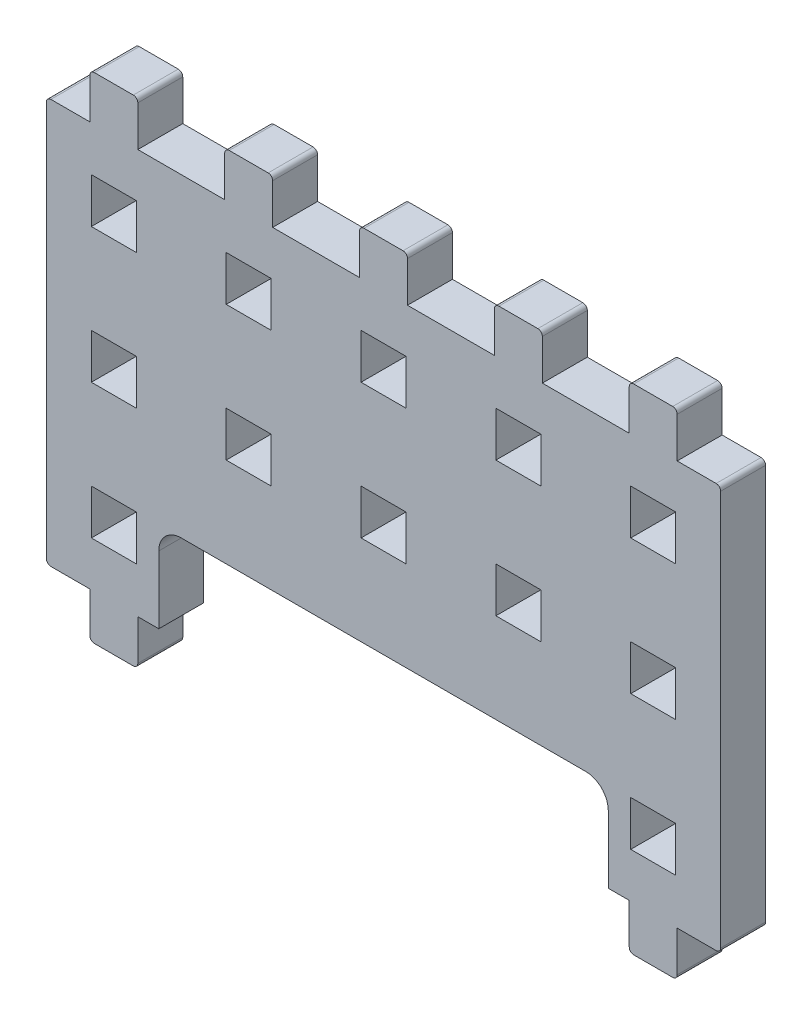
SolidWorks part; units mm, degrees
ref_plane "Alzado" through (0, 0, 0) normal (0, 0, 1) x (1, 0, 0)
ref_plane "Planta" through (0, 0, 0) normal (0, 1, 0) x (1, 0, 0)
ref_plane "Vista lateral" through (0, 0, 0) normal (1, 0, 0) x (0, 0, -1)
sketch "Model" plane through (0, 0, 0) normal (0, 0, 1) x (1, 0, 0)
  line L0 (12.4787, 293.1223) -> (12.4787, 290.1223)
  line L1 (15.4787, 293.1223) -> (12.4787, 293.1223)
  line L2 (15.4787, 290.1223) -> (15.4787, 293.1223)
  line L3 (12.4787, 290.1223) -> (15.4787, 290.1223)
  line L4 (21.4787, 293.1223) -> (21.4787, 290.1223)
  line L5 (24.4787, 293.1223) -> (21.4787, 293.1223)
  line L6 (24.4787, 290.1223) -> (24.4787, 293.1223)
  line L7 (21.4787, 290.1223) -> (24.4787, 290.1223)
  line L8 (30.4787, 293.1223) -> (30.4787, 290.1223)
  line L9 (33.4787, 293.1223) -> (30.4787, 293.1223)
  line L10 (33.4787, 290.1223) -> (33.4787, 293.1223)
  line L11 (30.4787, 290.1223) -> (33.4787, 290.1223)
  line L12 (12.4787, 275.1223) -> (12.4787, 272.1223)
  line L13 (15.4787, 275.1223) -> (12.4787, 275.1223)
  line L14 (15.4787, 272.1223) -> (15.4787, 275.1223)
  line L15 (12.4787, 272.1223) -> (15.4787, 272.1223)
  line L16 (12.4787, 284.1223) -> (12.4787, 281.1223)
  line L17 (15.4787, 284.1223) -> (12.4787, 284.1223)
  line L18 (15.4787, 281.1223) -> (15.4787, 284.1223)
  line L19 (12.4787, 281.1223) -> (15.4787, 281.1223)
  line L20 (21.4787, 284.1223) -> (21.4787, 281.1223)
  line L21 (24.4787, 284.1223) -> (21.4787, 284.1223)
  line L22 (24.4787, 281.1223) -> (24.4787, 284.1223)
  line L23 (21.4787, 281.1223) -> (24.4787, 281.1223)
  line L24 (30.4787, 284.1223) -> (30.4787, 281.1223)
  line L25 (33.4787, 284.1223) -> (30.4787, 284.1223)
  line L26 (33.4787, 281.1223) -> (33.4787, 284.1223)
  line L27 (30.4787, 281.1223) -> (33.4787, 281.1223)
  line L28 (48.4787, 293.1223) -> (48.4787, 290.1223)
  line L29 (51.4787, 293.1223) -> (48.4787, 293.1223)
  line L30 (51.4787, 290.1223) -> (51.4787, 293.1223)
  line L31 (48.4787, 290.1223) -> (51.4787, 290.1223)
  line L32 (48.4787, 275.1223) -> (48.4787, 272.1223)
  line L33 (51.4787, 275.1223) -> (48.4787, 275.1223)
  line L34 (51.4787, 272.1223) -> (51.4787, 275.1223)
  line L35 (48.4787, 272.1223) -> (51.4787, 272.1223)
  line L36 (48.4787, 284.1223) -> (48.4787, 281.1223)
  line L37 (51.4787, 284.1223) -> (48.4787, 284.1223)
  line L38 (51.4787, 281.1223) -> (51.4787, 284.1223)
  line L39 (48.4787, 281.1223) -> (51.4787, 281.1223)
  line L40 (39.4787, 293.1223) -> (39.4787, 290.1223)
  line L41 (42.4787, 293.1223) -> (39.4787, 293.1223)
  line L42 (42.4787, 290.1223) -> (42.4787, 293.1223)
  line L43 (39.4787, 290.1223) -> (42.4787, 290.1223)
  line L44 (39.4787, 284.1223) -> (39.4787, 281.1223)
  line L45 (42.4787, 284.1223) -> (39.4787, 284.1223)
  line L46 (42.4787, 281.1223) -> (42.4787, 284.1223)
  line L47 (39.4787, 281.1223) -> (42.4787, 281.1223)
  line L48 (9.4787, 295.8223) -> (9.4787, 269.4223)
  line L49 (12.3787, 298.8223) -> (12.3787, 296.1223)
  line L50 (15.5787, 296.1223) -> (15.5787, 298.8223)
  line L51 (12.6787, 299.1223) -> (15.2787, 299.1223)
  line L52 (9.7787, 296.1223) -> (12.3787, 296.1223)
  line L53 (24.5787, 296.1223) -> (30.3787, 296.1223)
  line L54 (21.3787, 298.8223) -> (21.3787, 296.1223)
  line L55 (24.5787, 296.1223) -> (24.5787, 298.8223)
  line L56 (21.6787, 299.1223) -> (24.2787, 299.1223)
  line L57 (15.5787, 296.1223) -> (21.3787, 296.1223)
  line L58 (30.3787, 298.8223) -> (30.3787, 296.1223)
  line L59 (33.5787, 296.1223) -> (33.5787, 298.8223)
  line L60 (30.6787, 299.1223) -> (33.2787, 299.1223)
  line L61 (12.3787, 266.4223) -> (12.3787, 269.1223)
  line L62 (15.5787, 269.1223) -> (15.5787, 266.4223)
  line L63 (12.6787, 266.1223) -> (15.2787, 266.1223)
  line L64 (9.7787, 269.1223) -> (12.3787, 269.1223)
  line L65 (46.9787, 269.1223) -> (48.3787, 269.1223)
  line L66 (54.4787, 295.8223) -> (54.4787, 269.4223)
  line L67 (33.5787, 296.1223) -> (39.3787, 296.1223)
  line L68 (48.3787, 298.8223) -> (48.3787, 296.1223)
  line L69 (51.5787, 296.1223) -> (51.5787, 298.8223)
  line L70 (48.6787, 299.1223) -> (51.2787, 299.1223)
  line L71 (51.5787, 296.1223) -> (54.1787, 296.1223)
  line L72 (48.3787, 266.4223) -> (48.3787, 269.1223)
  line L73 (51.5787, 269.1223) -> (51.5787, 266.4223)
  line L74 (48.6787, 266.1223) -> (51.2787, 266.1223)
  line L75 (51.5787, 269.1223) -> (54.1787, 269.1223)
  line L76 (18.4787, 275.1223) -> (45.4787, 275.1223)
  line L77 (16.9787, 273.6223) -> (16.9787, 269.1223)
  line L78 (46.9787, 273.6223) -> (46.9787, 269.1223)
  line L79 (15.5787, 269.1223) -> (16.9787, 269.1223)
  line L80 (39.3787, 298.8223) -> (39.3787, 296.1223)
  line L81 (42.5787, 296.1223) -> (42.5787, 298.8223)
  line L82 (39.6787, 299.1223) -> (42.2787, 299.1223)
  line L83 (42.5787, 296.1223) -> (48.3787, 296.1223)
  arc A0 (12.6787, 299.1223) -> (12.3787, 298.8223) centre (12.6787, 298.8223) ccw
  arc A1 (15.5787, 298.8223) -> (15.2787, 299.1223) centre (15.2787, 298.8223) ccw
  arc A2 (9.7787, 296.1223) -> (9.4787, 295.8223) centre (9.7787, 295.8223) ccw
  arc A3 (21.6787, 299.1223) -> (21.3787, 298.8223) centre (21.6787, 298.8223) ccw
  arc A4 (24.5787, 298.8223) -> (24.2787, 299.1223) centre (24.2787, 298.8223) ccw
  arc A5 (30.6787, 299.1223) -> (30.3787, 298.8223) centre (30.6787, 298.8223) ccw
  arc A6 (33.5787, 298.8223) -> (33.2787, 299.1223) centre (33.2787, 298.8223) ccw
  arc A7 (12.3787, 266.4223) -> (12.6787, 266.1223) centre (12.6787, 266.4223) ccw
  arc A8 (15.2787, 266.1223) -> (15.5787, 266.4223) centre (15.2787, 266.4223) ccw
  arc A9 (9.4787, 269.4223) -> (9.7787, 269.1223) centre (9.7787, 269.4223) ccw
  arc A10 (54.4787, 295.8223) -> (54.1787, 296.1223) centre (54.1787, 295.8223) ccw
  arc A11 (48.6787, 299.1223) -> (48.3787, 298.8223) centre (48.6787, 298.8223) ccw
  arc A12 (51.5787, 298.8223) -> (51.2787, 299.1223) centre (51.2787, 298.8223) ccw
  arc A13 (54.1787, 269.1223) -> (54.4787, 269.4223) centre (54.1787, 269.4223) ccw
  arc A14 (48.3787, 266.4223) -> (48.6787, 266.1223) centre (48.6787, 266.4223) ccw
  arc A15 (51.2787, 266.1223) -> (51.5787, 266.4223) centre (51.2787, 266.4223) ccw
  arc A16 (18.4787, 275.1223) -> (16.9787, 273.6223) centre (18.4787, 273.6223) ccw
  arc A17 (46.9787, 273.6223) -> (45.4787, 275.1223) centre (45.4787, 273.6223) ccw
  arc A18 (39.6787, 299.1223) -> (39.3787, 298.8223) centre (39.6787, 298.8223) ccw
  arc A19 (42.5787, 298.8223) -> (42.2787, 299.1223) centre (42.2787, 298.8223) ccw
extrude "Saliente-Extruir1" add sketch "Model" along normal blind 3
